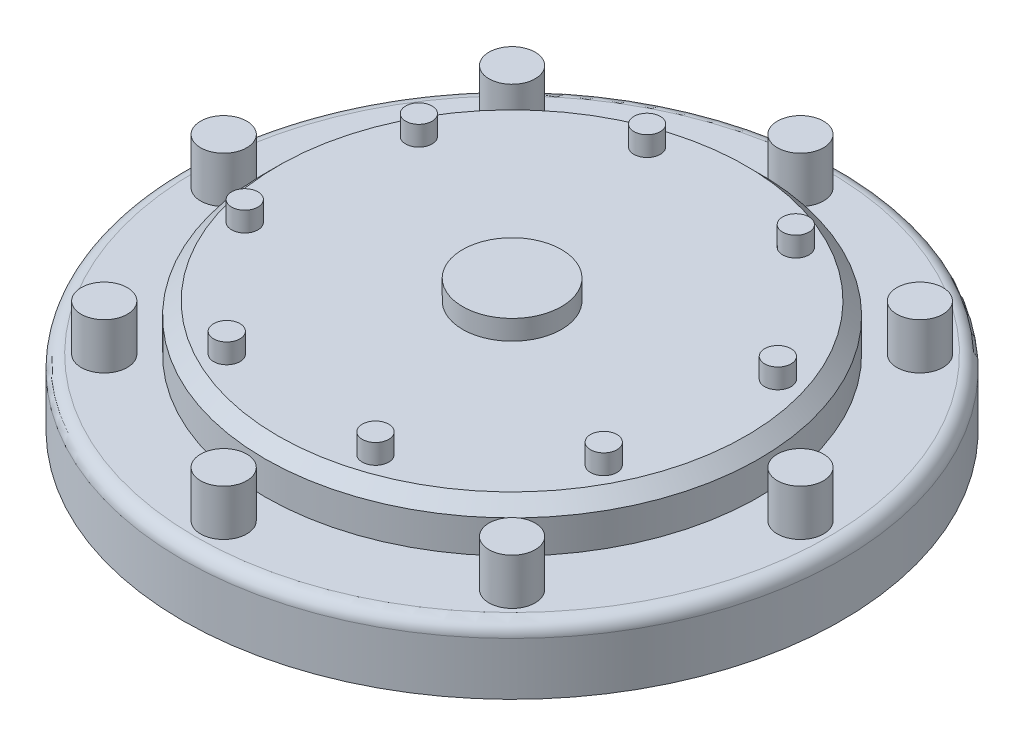
SolidWorks part; units mm, degrees
ref_plane "Front Plane" through (0, 0, 0) normal (0, 0, 1) x (1, 0, 0)
ref_plane "Top Plane" through (0, 0, 0) normal (0, 1, 0) x (1, 0, 0)
ref_plane "Right Plane" through (0, 0, 0) normal (1, 0, 0) x (0, 0, -1)
sketch "Sketch2" plane through (0, 0, 0) normal (0, 1, 0) x (1, 0, 0)
  circle A0 centre (0, 0) radius 50
  dimension "D1" = 100
extrude "Boss-Extrude1" add sketch "Sketch2" along normal blind 10
sketch "Sketch4" plane through (0, 10, 0) normal (0, 1, 0) x (1, 0, 0)
  circle A0 centre (0, 0) radius 37.5
  dimension "D1" = 75
extrude "Boss-Extrude3" add sketch "Sketch4" along normal blind 7
sketch "Sketch5" plane through (0, 10, 0) normal (0, 1, 0) x (1, 0, 0)
  line L0 (0, 0) -> (43.75, 0) construction
  circle A0 centre (43.75, 0) radius 3.5
  dimension "D2" = 7
  dimension "D1" = 43.75
extrude "Boss-Extrude4" add sketch "Sketch5" along normal up to surface (7 mm away) up to face at (0, 17, 37.5)
pattern_circular "CirPattern1" count 8 over 360 about axis through (0, 0, 0) along (0, 1, 0) of "Boss-Extrude4"
sketch "Sketch6" plane through (0, 17, 0) normal (0, 1, 0) x (1, 0, 0)
  line L0 (0, 0) -> (37.5, 0) construction
  line L1 (0, 0) -> (30.4338, 9.8885) construction
  circle A0 centre (0, 0) radius 37.5 construction
  circle A1 centre (30.4338, 9.8885) radius 2
  dimension "D3" = 4
  dimension "D1" = 18
  dimension "D2" = 32
extrude "Boss-Extrude5" add sketch "Sketch6" along normal blind 3
pattern_circular "CirPattern2" count 8 over 360 about axis through (-0.0868, 0, 0.0282) along (0, 1, 0) of "Boss-Extrude5"
chamfer "Chamfer1" distance 2 angle 45 1 edges at (0, 17, 37.5)
fillet "Fillet1" radius 2 1 edges at (0, 10, 50)
sketch "Sketch7" plane through (0, 0, 0) normal (0, -1, 0) x (1, 0, 0)
  circle A0 centre (0, 0) radius 7.5
  dimension "D1" = 15
extrude "Boss-Extrude6" add sketch "Sketch7" along normal blind 20 and the other way blind 20
